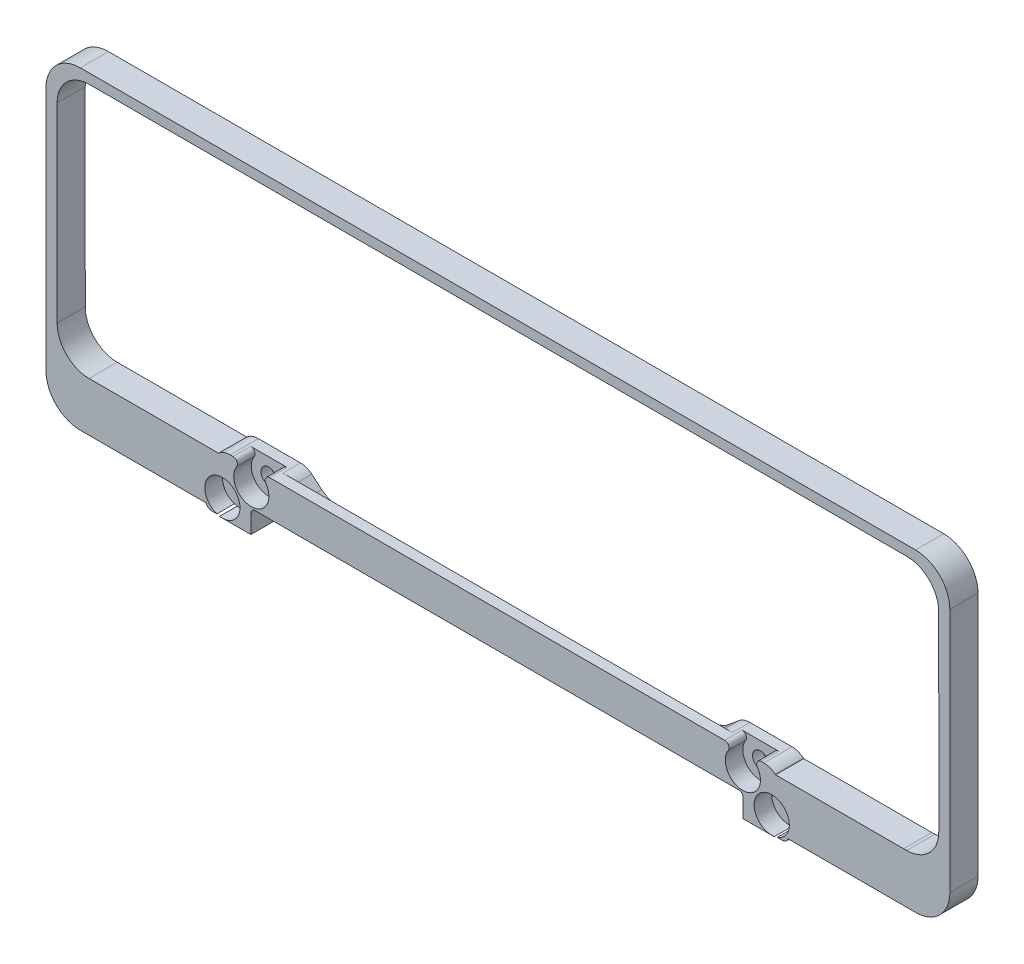
SolidWorks part; units mm, degrees
ref_plane "前视基准面" through (0, 0, 0) normal (0, 0, 1) x (1, 0, 0)
ref_plane "上视基准面" through (0, 0, 0) normal (0, 1, 0) x (1, 0, 0)
ref_plane "右视基准面" through (0, 0, 0) normal (1, 0, 0) x (0, 0, -1)
sketch "草图1" plane through (0, 0, 0) normal (0, 0, 1) x (1, 0, 0)
  line L10 (-32.44, 5.005) -> (-31.75, 5.005)
  line L11 (-31.522, 4.9) -> (-28, 4.9)
  line L12 (-28, 4.9) -> (-28, 6.9967)
  line L13 (-27.5, 7.4967) -> (-22.1814, 7.4967)
  line L14 (-22.1814, 7.4967) -> (-22.1814, 9.6269)
  line L15 (-23.1421, 10.1559) -> (-24.2687, 11.1058)
  line L16 (-25.5578, 11.5767) -> (-30.3471, 11.5767)
  line L17 (-31.6362, 11.1058) -> (-32.4291, 10.4373)
  line L18 (-33.14, 8.9082) -> (-33.14, 5.705)
  line L19 (-32.44, 5.005) -> (-31.75, 5.005)
  line L20 (-31.522, 4.9) -> (-28, 4.9)
  line L21 (-28, 4.9) -> (-28, 6.9967)
  line L22 (-27.5, 7.4967) -> (-22.1814, 7.4967)
  line L23 (-22.1814, 7.4967) -> (-22.1814, 9.6269)
  line L24 (-23.1421, 10.1559) -> (-24.2687, 11.1058)
  line L25 (-25.5578, 11.5767) -> (-30.3471, 11.5767)
  line L26 (-31.6362, 11.1058) -> (-32.4291, 10.4373)
  line L27 (-33.14, 8.9082) -> (-33.14, 5.705)
  line L28 (28, 6.9967) -> (28, 4.9)
  line L29 (28, 4.9) -> (31.522, 4.9)
  line L30 (31.75, 5.005) -> (32.44, 5.005)
  line L31 (33.14, 5.705) -> (33.14, 8.9082)
  line L32 (32.4291, 10.4373) -> (31.6362, 11.1058)
  line L33 (30.3471, 11.5767) -> (25.5578, 11.5767)
  line L34 (24.2687, 11.1058) -> (23.1421, 10.1559)
  line L35 (22.1814, 9.6269) -> (22.1814, 7.4967)
  line L36 (22.1814, 7.4967) -> (27.5, 7.4967)
  line L37 (28, 6.9967) -> (28, 4.9)
  line L38 (28, 4.9) -> (31.522, 4.9)
  line L39 (31.75, 5.005) -> (32.44, 5.005)
  line L40 (33.14, 5.705) -> (33.14, 8.9082)
  line L41 (32.4291, 10.4373) -> (31.6362, 11.1058)
  line L42 (30.3471, 11.5767) -> (25.5578, 11.5767)
  line L43 (24.2687, 11.1058) -> (23.1421, 10.1559)
  line L44 (22.1814, 9.6269) -> (22.1814, 7.4967)
  line L45 (22.1814, 7.4967) -> (27.5, 7.4967)
  circle A1 centre (-27.9525, 9.6767) radius 0.9 construction
  circle A2 centre (-27.9525, 9.6767) radius 0.9
  circle A3 centre (-31.24, 6.905) radius 0.8 construction
  circle A4 centre (-31.24, 6.905) radius 0.8
  circle A5 centre (27.9525, 9.6767) radius 0.9 construction
  circle A6 centre (27.9525, 9.6767) radius 0.9
  circle A7 centre (31.24, 6.905) radius 0.8 construction
  arc A8 (-33.14, 5.705) -> (-32.44, 5.005) centre (-32.44, 5.705) ccw
  arc A9 (-31.522, 4.9) -> (-31.75, 5.005) centre (-31.75, 4.705) ccw
  arc A10 (-27.5, 7.4967) -> (-28, 6.9967) centre (-27.5, 6.9967) ccw
  arc A11 (-23.1421, 10.1559) -> (-22.1814, 9.6269) centre (-21.3373, 12.2967) ccw
  arc A12 (-24.2687, 11.1058) -> (-25.5578, 11.5767) centre (-25.5578, 9.5767) ccw
  arc A13 (-30.3471, 11.5767) -> (-31.6362, 11.1058) centre (-30.3471, 9.5767) ccw
  arc A14 (-32.4291, 10.4373) -> (-33.14, 8.9082) centre (-31.14, 8.9082) ccw
  arc A15 (-33.14, 5.705) -> (-32.44, 5.005) centre (-32.44, 5.705) ccw
  arc A16 (-31.522, 4.9) -> (-31.75, 5.005) centre (-31.75, 4.705) ccw
  arc A17 (-27.5, 7.4967) -> (-28, 6.9967) centre (-27.5, 6.9967) ccw
  arc A18 (-23.1421, 10.1559) -> (-22.1814, 9.6269) centre (-21.3373, 12.2967) ccw
  arc A19 (-24.2687, 11.1058) -> (-25.5578, 11.5767) centre (-25.5578, 9.5767) ccw
  arc A20 (-30.3471, 11.5767) -> (-31.6362, 11.1058) centre (-30.3471, 9.5767) ccw
  arc A21 (-32.4291, 10.4373) -> (-33.14, 8.9082) centre (-31.14, 8.9082) ccw
  circle A22 centre (31.24, 6.905) radius 0.8
  arc A26 (31.75, 5.005) -> (31.522, 4.9) centre (31.75, 4.705) ccw
  arc A27 (32.44, 5.005) -> (33.14, 5.705) centre (32.44, 5.705) ccw
  arc A28 (33.14, 8.9082) -> (32.4291, 10.4373) centre (31.14, 8.9082) ccw
  arc A29 (31.6362, 11.1058) -> (30.3471, 11.5767) centre (30.3471, 9.5767) ccw
  arc A30 (25.5578, 11.5767) -> (24.2687, 11.1058) centre (25.5578, 9.5767) ccw
  arc A31 (22.1814, 9.6269) -> (23.1421, 10.1559) centre (21.3373, 12.2967) ccw
  arc A32 (28, 6.9967) -> (27.5, 7.4967) centre (27.5, 6.9967) ccw
  arc A33 (31.75, 5.005) -> (31.522, 4.9) centre (31.75, 4.705) ccw
  arc A34 (32.44, 5.005) -> (33.14, 5.705) centre (32.44, 5.705) ccw
  arc A35 (33.14, 8.9082) -> (32.4291, 10.4373) centre (31.14, 8.9082) ccw
  arc A36 (31.6362, 11.1058) -> (30.3471, 11.5767) centre (30.3471, 9.5767) ccw
  arc A37 (25.5578, 11.5767) -> (24.2687, 11.1058) centre (25.5578, 9.5767) ccw
  arc A38 (22.1814, 9.6269) -> (23.1421, 10.1559) centre (21.3373, 12.2967) ccw
  arc A39 (28, 6.9967) -> (27.5, 7.4967) centre (27.5, 6.9967) ccw
  dimension "D1" = 0
  dimension "D2" = 0
extrude "凸台-拉伸1" add sketch "草图1" along normal offset from surface (3.2 mm away) 0.2
sketch "草图2" plane through (0, 0, 3.2) normal (0, 0, 1) x (1, 0, 0)
  line L3 (-25.5578, 11.5767) -> (25.5578, 11.5767)
  line L4 (25.5578, 11.5767) -> (25.5578, 7.4967)
  line L5 (22.1814, 7.4967) -> (27.5, 7.4967) construction
  line L9 (25.5578, 7.4967) -> (-25.5578, 7.4967)
  line L10 (-27.5, 7.4967) -> (-22.1814, 7.4967) construction
  line L11 (-25.5578, 7.4967) -> (-25.5578, 11.5767)
extrude "凸台-拉伸2" add sketch "草图2" against normal blind 1.2
sketch "草图3" plane through (0, 0, 3.2) normal (0, 0, 1) x (1, 0, 0)
  line L1 (46.2409, 11.0744) -> (24.6546, 11.0726) construction
  line L3 (50.2353, 36.4185) -> (50.237, 14.7185) construction
  line L5 (-46.4025, 40.048) -> (46.5977, 40.0555) construction
  line L6 (-50.0378, 14.7103) -> (-50.0395, 36.4103) construction
  line L7 (-24.4548, 11.0751) -> (-46.4002, 11.0733) construction
  line L9 (46.2409, 11.0744) -> (31.6748, 11.0732)
  line L11 (50.2353, 36.4185) -> (50.237, 14.7185)
  line L13 (-46.4025, 40.048) -> (46.5977, 40.0555)
  line L14 (-50.0378, 14.7103) -> (-50.0395, 36.4103)
  line L16 (-31.6733, 11.0745) -> (-46.4002, 11.0733)
  line L19 (-47.3996, 5.4732) -> (-35.3996, 5.4742) construction
  line L20 (-47.3996, 5.4732) -> (-33.1009, 5.4743)
  line L22 (35.6004, 5.48) -> (47.6004, 5.4809) construction
  line L23 (51.5001, 9.3812) -> (51.4978, 37.2812) construction
  line L24 (47.5975, 41.1809) -> (-47.4025, 41.1732) construction
  line L25 (-51.3022, 37.2729) -> (-51.2999, 9.3729) construction
  line L26 (33.1028, 5.4797) -> (47.6004, 5.4809)
  line L27 (51.5001, 9.3812) -> (51.4978, 37.2812)
  line L28 (47.5975, 41.1809) -> (-47.4025, 41.1732)
  line L29 (-51.3022, 37.2729) -> (-51.2999, 9.3729)
  line L30 (33.14, 5.705) -> (33.14, 8.9082) construction
  line L31 (32.4291, 10.4373) -> (31.6362, 11.1058) construction
  line L32 (33.14, 5.705) -> (33.14, 8.9082)
  line L33 (32.4291, 10.4373) -> (31.6748, 11.0732)
  line L34 (-33.14, 8.9082) -> (-33.14, 5.705) construction
  line L35 (-31.6362, 11.1058) -> (-32.4291, 10.4373) construction
  line L36 (-33.14, 8.9082) -> (-33.14, 5.705)
  line L37 (-31.6733, 11.0745) -> (-32.4291, 10.4373)
  arc A1 (46.2409, 11.0744) -> (46.6, 11.0809) centre (46.2401, 21.0744) ccw construction
  arc A3 (46.6, 11.0809) -> (50.237, 14.7185) centre (46.5997, 14.7182) ccw construction
  arc A5 (50.2353, 36.4185) -> (46.5977, 40.0555) centre (46.5979, 36.4182) ccw construction
  arc A7 (-46.4025, 40.048) -> (-50.0395, 36.4103) centre (-46.4022, 36.4106) ccw construction
  arc A11 (-50.0378, 14.7103) -> (-46.4002, 11.0733) centre (-46.4005, 14.7106) ccw construction
  arc A13 (46.2409, 11.0744) -> (46.6, 11.0809) centre (46.2401, 21.0744) ccw
  arc A15 (46.6, 11.0809) -> (50.237, 14.7185) centre (46.5997, 14.7182) ccw
  arc A17 (50.2353, 36.4185) -> (46.5977, 40.0555) centre (46.5979, 36.4182) ccw
  arc A19 (-46.4025, 40.048) -> (-50.0395, 36.4103) centre (-46.4022, 36.4106) ccw
  arc A20 (-50.0378, 14.7103) -> (-46.4002, 11.0733) centre (-46.4005, 14.7106) ccw
  arc A22 (-51.2999, 9.3729) -> (-47.3996, 5.4732) centre (-47.3999, 9.3732) ccw construction
  arc A23 (-51.2999, 9.3729) -> (-47.3996, 5.4732) centre (-47.3999, 9.3732) ccw
  arc A24 (47.6004, 5.4809) -> (51.5001, 9.3812) centre (47.6001, 9.3809) ccw construction
  arc A25 (51.4978, 37.2812) -> (47.5975, 41.1809) centre (47.5978, 37.2809) ccw construction
  arc A26 (-47.4025, 41.1732) -> (-51.3022, 37.2729) centre (-47.4022, 37.2732) ccw construction
  arc A27 (47.6004, 5.4809) -> (51.5001, 9.3812) centre (47.6001, 9.3809) ccw
  arc A28 (51.4978, 37.2812) -> (47.5975, 41.1809) centre (47.5978, 37.2809) ccw
  arc A29 (-47.4025, 41.1732) -> (-51.3022, 37.2729) centre (-47.4022, 37.2732) ccw
  arc A30 (33.14, 8.9082) -> (32.4291, 10.4373) centre (31.14, 8.9082) ccw construction
  arc A31 (33.14, 8.9082) -> (32.4291, 10.4373) centre (31.14, 8.9082) ccw
  arc A32 (32.44, 5.005) -> (33.14, 5.705) centre (32.44, 5.705) ccw construction
  arc A33 (-33.14, 5.705) -> (-32.44, 5.005) centre (-32.44, 5.705) ccw construction
  arc A34 (-32.4291, 10.4373) -> (-33.14, 8.9082) centre (-31.14, 8.9082) ccw construction
  arc A36 (33.1028, 5.4797) -> (33.14, 5.705) centre (32.44, 5.705) ccw
  arc A37 (-33.14, 5.705) -> (-33.1009, 5.4743) centre (-32.44, 5.705) ccw
  arc A38 (-32.4291, 10.4373) -> (-33.14, 8.9082) centre (-31.14, 8.9082) ccw
extrude "凸台-拉伸3" add sketch "草图3" against normal up to vertex (3.2 mm away) up to point (31.6362, 11.1057, 0)
sketch "草图4" plane through (0, 0, 3.2) normal (0, 0, 1) x (1, 0, 0)
  circle A0 centre (-27.9525, 9.6767) radius 2
  circle A1 centre (27.9525, 9.6767) radius 2
  circle A2 centre (-31.24, 6.905) radius 2
  circle A3 centre (31.24, 6.905) radius 2
  dimension "D1" = 4
extrude "切除-拉伸1" cut sketch "草图4" against normal blind 2
fillet "圆角1" radius 0.5 4 edges at (-28.5769, 11.5767, 2.2) (-27.328, 11.5767, 2.2) (28.5769, 11.5767, 2.2) (27.328, 11.5767, 2.2)
